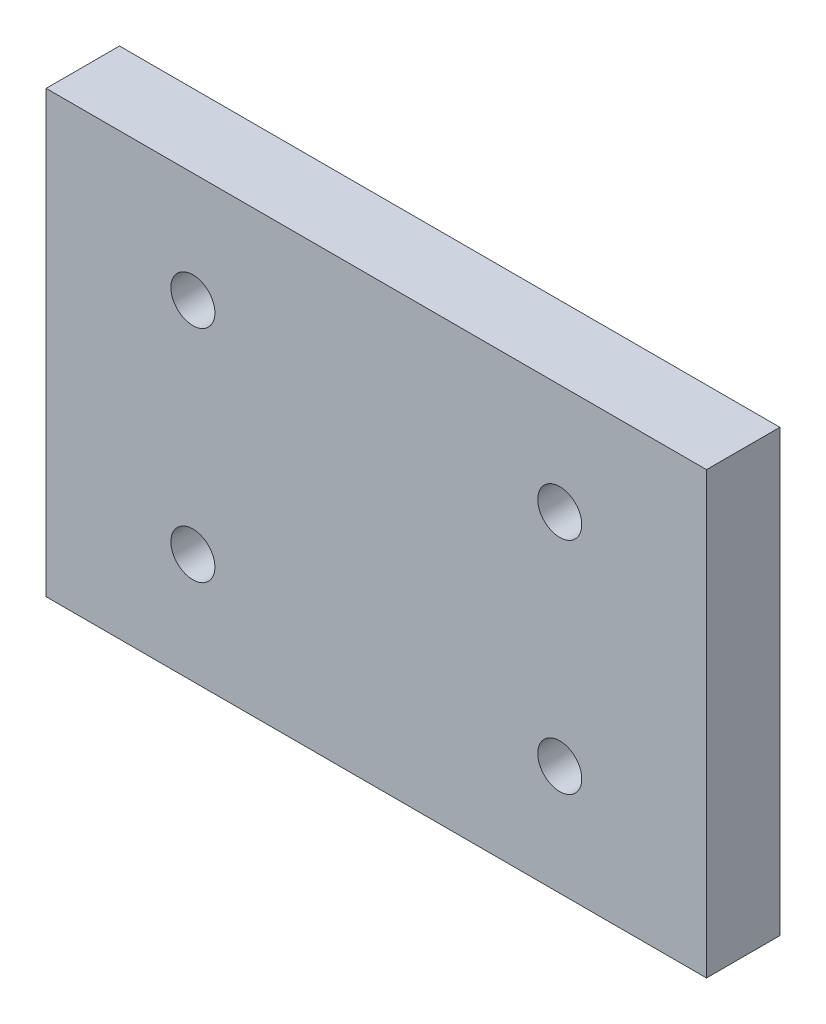
SolidWorks part; units mm, degrees
ref_plane "Plano frontal" through (0, 0, 0) normal (0, 0, 1) x (1, 0, 0)
ref_plane "Plano superior" through (0, 0, 0) normal (0, 1, 0) x (1, 0, 0)
ref_plane "Plano direito" through (0, 0, 0) normal (1, 0, 0) x (0, 0, -1)
sketch "Esboço1" plane through (0, 0, 0) normal (0, 0, 1) x (1, 0, 0)
  line L0 (-90, 0) -> (-90, 120)
  line L1 (-90, 120) -> (90, 120)
  line L2 (90, 120) -> (90, 0)
  line L3 (90, 0) -> (-90, 0)
  line L4 (-50, 60) -> (50, 60) construction
  dimension "D1" = 120
  dimension "D2" = 180
  dimension "D3" = 100
extrude "Ressalto-extrusão1" add sketch "Esboço1" along normal blind 20
sketch "Esboço2" plane through (0, 0, 0) normal (0, 0, -1) x (-1, 0, 0)
  line L0 (-50, 90) -> (-50, 30) construction
  line L2 (-90, 120) -> (90, 120) construction
  line L3 (-90, 0) -> (-90, 120) construction
  line L4 (0, 0) -> (0, 120) construction
  line L5 (50, 90) -> (50, 30) construction
  circle A0 centre (-50, 90) radius 6
  circle A1 centre (-50, 30) radius 6
  circle A2 centre (50, 30) radius 6
  circle A3 centre (50, 90) radius 6
  dimension "D1" = 12
  dimension "D2" = 12
  dimension "D3" = 60
  dimension "D4" = 30
  dimension "D5" = 40
extrude "Corte-extrusão1" cut sketch "Esboço2" against normal through all and the other way through all
